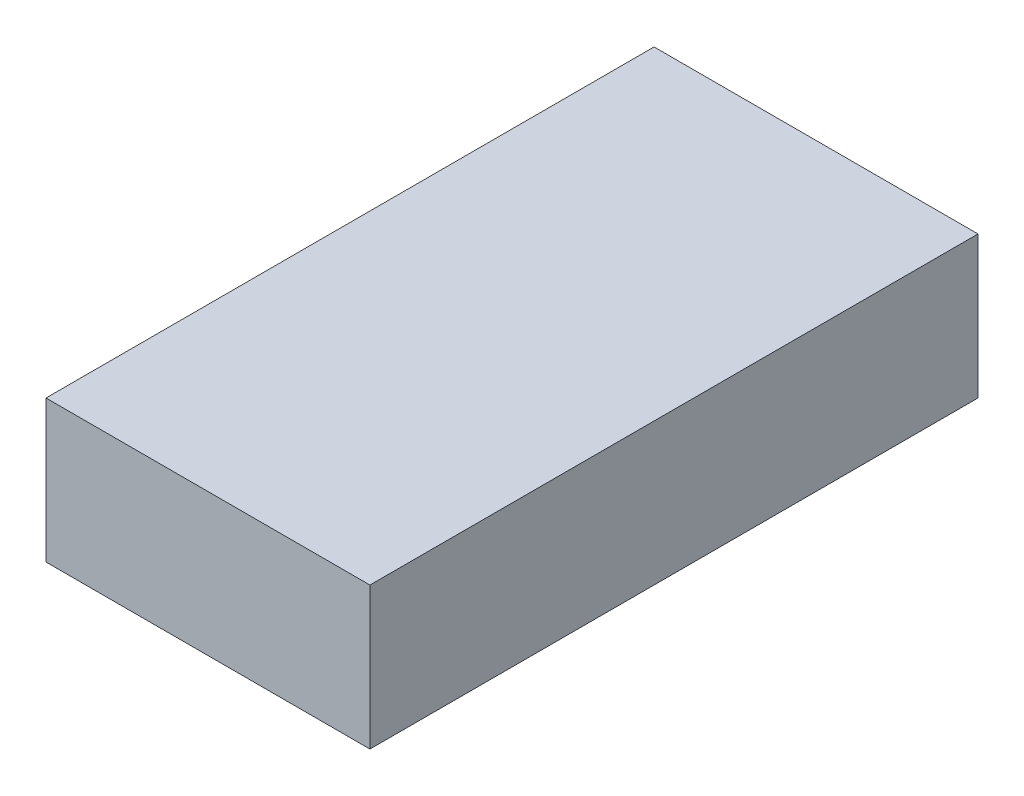
SolidWorks part; units mm, degrees
ref_plane "Front Plane" through (0, 0, 0) normal (0, 0, 1) x (1, 0, 0)
ref_plane "Top Plane" through (0, 0, 0) normal (0, 1, 0) x (1, 0, 0)
ref_plane "Right Plane" through (0, 0, 0) normal (1, 0, 0) x (0, 0, -1)
sketch "Sketch1" plane through (0, 0, 0) normal (0, 0, 1) x (1, 0, 0)
  line L1 (57, -25) -> (-57, -25)
  line L2 (57, -25) -> (57, 25)
  line L3 (57, 25) -> (-57, 25)
  line L4 (-57, -25) -> (-57, 25)
  line L5 (57, -25) -> (-57, 25) construction
  line L6 (57, 25) -> (-57, -25) construction
  point P0 (0, 0)
extrude "Boss-Extrude1" add sketch "Sketch1" along normal blind 214
